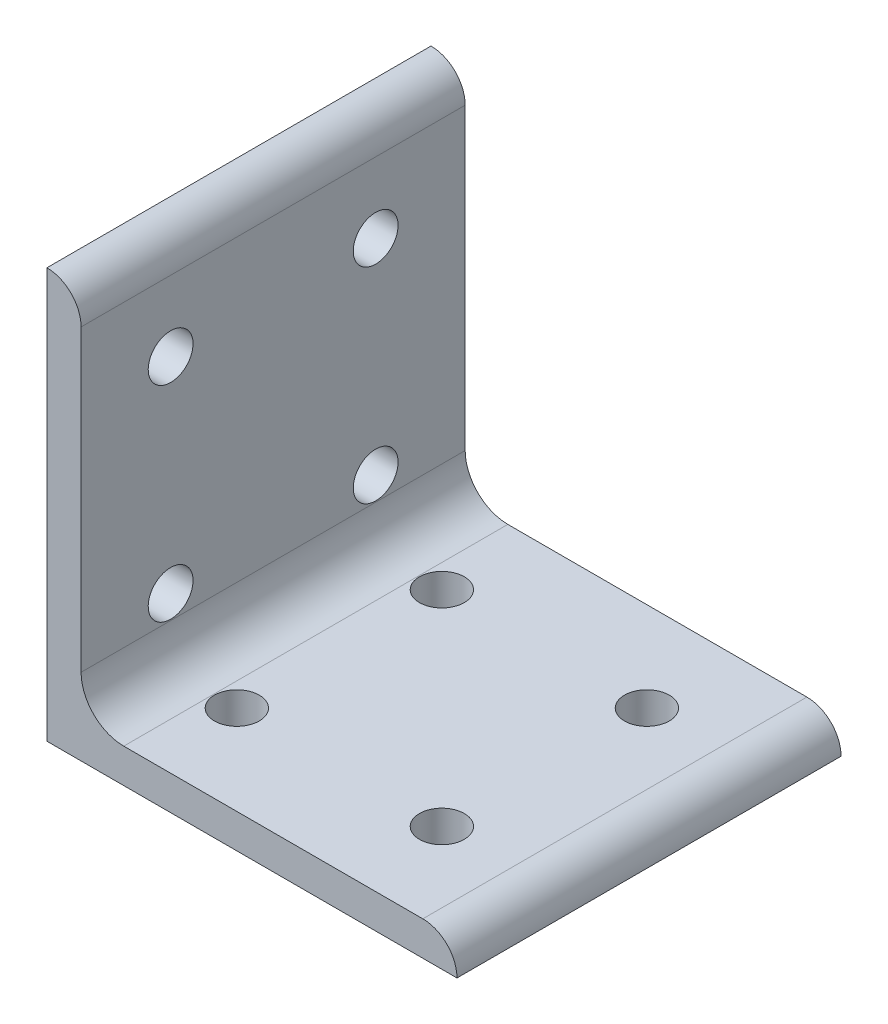
SolidWorks part; units mm, degrees
ref_plane "Front Plane" through (0, 0, 0) normal (0, 0, 1) x (1, 0, 0)
ref_plane "Top Plane" through (0, 0, 0) normal (0, 1, 0) x (1, 0, 0)
ref_plane "Right Plane" through (0, 0, 0) normal (1, 0, 0) x (0, 0, -1)
sketch "Sketch1" plane through (0, 0, 0) normal (0, 0, 1) x (1, 0, 0)
  line L0 (0, 0) -> (0, 76.2)
  line L1 (6.35, 69.85) -> (6.35, 76.2) construction
  line L2 (6.35, 69.85) -> (6.35, 14.2748)
  line L3 (14.2748, 6.35) -> (69.85, 6.35)
  line L4 (6.35, 76.2) -> (0, 76.2) construction
  line L5 (76.2, 0) -> (0, 0)
  line L6 (69.85, 6.35) -> (76.2, 6.35) construction
  line L7 (76.2, 6.35) -> (76.2, 0) construction
  arc A0 (6.35, 69.85) -> (0, 76.2) centre (0, 69.85) ccw
  arc A1 (76.2, 0) -> (69.85, 6.35) centre (69.85, 0) ccw
  arc A2 (6.35, 14.2748) -> (14.2748, 6.35) centre (14.2748, 14.2748) ccw
  point P10 (6.35, 73.025)
  dimension "E" = 7.9248
  dimension "D" = 6.35
  dimension "C" = 76.2
  dimension "B" = 76.2
extrude "Boss-Extrude1" add sketch "Sketch1" along normal mid plane 71.374
sketch "Sketch2" plane through (0, 0, 0) normal (0, 1, 0) x (1, 0, 0)
  line L0 (0, -19.05) -> (18.6531, -19.05) construction
  line L1 (18.6531, -19.05) -> (56.7531, -19.05) construction
  line L2 (0, -19.05) -> (0, 19.05) construction
  line L3 (0, 19.05) -> (18.6531, 19.05) construction
  line L4 (56.7531, 19.05) -> (56.7531, -19.05) construction
  line L5 (0, -19.05) -> (0, -35.687) construction
  line L6 (18.6531, -19.05) -> (18.6531, 19.05) construction
  line L7 (18.6531, 19.05) -> (56.7531, 19.05) construction
  circle A0 centre (18.6531, -19.05) radius 4.1656
  circle A1 centre (56.7531, -19.05) radius 4.1656
  circle A2 centre (18.6531, 19.05) radius 4.1656
  circle A3 centre (56.7531, 19.05) radius 4.1656
extrude "Cut-Extrude1" cut sketch "Sketch2" along normal through all
sketch "Sketch3" plane through (0, 0, 0) normal (1, 0, 0) x (0, 0, -1)
  line L0 (-19.05, 0) -> (-19.05, 18.6531) construction
  line L1 (-19.05, 18.6531) -> (-19.05, 56.7531) construction
  line L2 (19.05, 0) -> (19.05, 18.6531) construction
  line L3 (19.05, 18.6531) -> (-19.05, 18.6531) construction
  line L4 (19.05, 18.6531) -> (19.05, 56.7531) construction
  line L5 (19.05, 56.7531) -> (-19.05, 56.7531) construction
  circle A0 centre (-19.05, 18.6531) radius 4.1656
  circle A1 centre (-19.05, 56.7531) radius 4.1656
  circle A2 centre (19.05, 18.6531) radius 4.1656
  circle A3 centre (19.05, 56.7531) radius 4.1656
  dimension "D1" = 18.6531
  dimension "D2" = 38.1
extrude "Cut-Extrude2" cut sketch "Sketch3" along normal through all
equation "\"E@Sketch3\" = \"E@Sketch2\""
equation "\"D1@Sketch3\" = \"D1@Sketch2\""
equation "\"D2@Sketch3\" = \"D2@Sketch2\""
